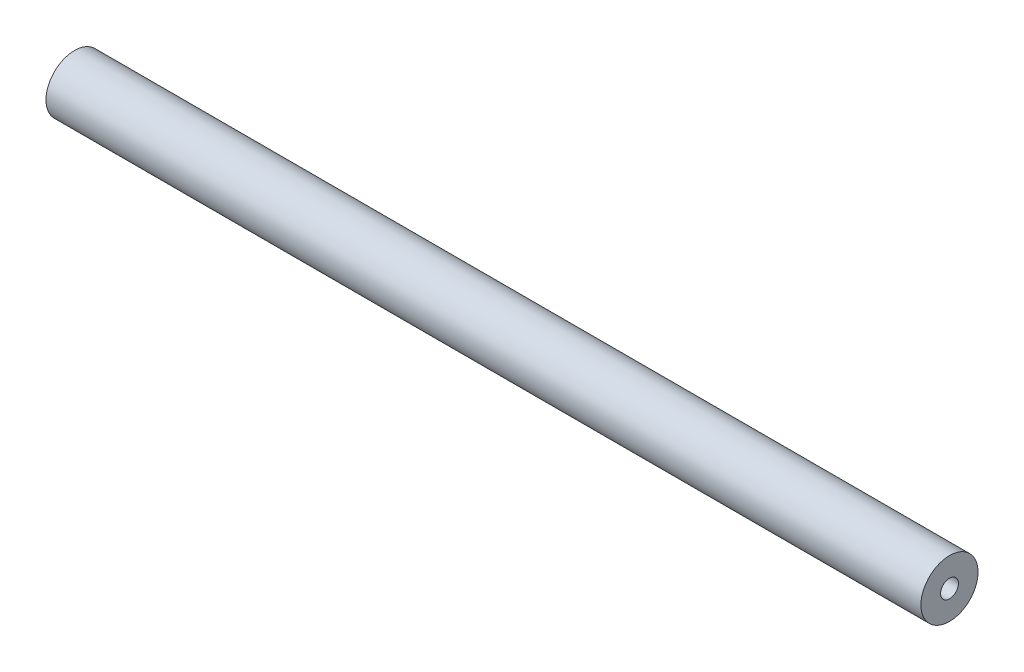
SolidWorks part; units mm, degrees
material "6061 합금"
ref_plane "정면" through (0, 0, 0) normal (0, 0, 1) x (1, 0, 0)
ref_plane "윗면" through (0, 0, 0) normal (0, 1, 0) x (1, 0, 0)
ref_plane "우측면" through (0, 0, 0) normal (1, 0, 0) x (0, 0, -1)
sketch "스케치2" plane through (0, 0, 0) normal (1, 0, 0) x (0, 0, -1)
  circle A0 centre (0, 0) radius 4
  dimension "D1" = 8
extrude "보스-돌출1" add sketch "스케치2" along normal up to surface (61.25 mm away)
hole_wizard "M3x0.5 나사 구멍1" positions "스케치3" profile "스케치4" tap size "M3x0.5" standard "Ansi Metric"
sketch "스케치3" plane through (61.25, 0, 0) normal (1, 0, 0) x (0, 0, -1)
  point P0 (0, 0)
sketch "스케치4" plane through (61.25, 0, 0) normal (0, 1, 0) x (0, 0, -1)
  line L0 (0, 0) -> (0, 22.2511)
  line L1 (0, 22.2511) -> (1.25, 21.5)
  line L2 (1.25, 21.5) -> (1.25, 0)
  line L5 (1.25, 0) -> (0, 0)
  line L10 (0, 22.2511) -> (-1.25, 21.5) construction
  line L11 (0, -6.35) -> (0, 107.95) construction
  dimension "탭 드릴 지름" = 2.5
  dimension "탭 드릴 깊이" = 21.5
  dimension "드릴 각도" = 118
cosmetic thread "구멍 나사산1"
mirror "대칭 복사1" about plane through (0, 0, 0) normal (1, 0, 0) of "M3x0.5 나사 구멍1", "보스-돌출1"
